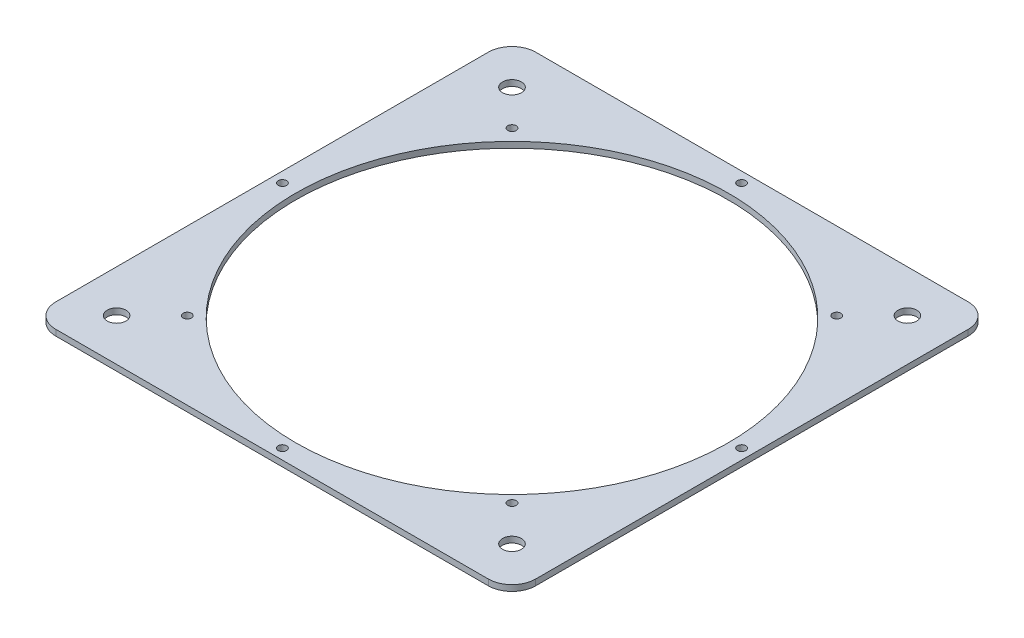
SolidWorks part; units mm, degrees
ref_plane "Front Plane" through (0, 0, 0) normal (0, 0, 1) x (1, 0, 0)
ref_plane "Top Plane" through (0, 0, 0) normal (0, 1, 0) x (1, 0, 0)
ref_plane "Right Plane" through (0, 0, 0) normal (1, 0, 0) x (0, 0, -1)
sketch "Sketch1" plane through (0, 0, 0) normal (0, 1, 0) x (1, 0, 0)
  line L1 (-128.5875, -128.5875) -> (128.5875, -128.5875)
  line L2 (-128.5875, -128.5875) -> (-128.5875, 128.5875)
  line L3 (-128.5875, 128.5875) -> (128.5875, 128.5875)
  line L4 (128.5875, -128.5875) -> (128.5875, 128.5875)
  line L5 (-128.5875, -128.5875) -> (128.5875, 128.5875) construction
  line L6 (-128.5875, 128.5875) -> (128.5875, -128.5875) construction
  point P0 (0, 0)
  dimension "D1" = 257.175
extrude "Boss-Extrude1" add sketch "Sketch1" along normal blind 3.175
sketch "Sketch2" plane through (0, 3.175, 0) normal (0, 1, 0) x (1, 0, 0)
  line L0 (-128.5875, 128.5875) -> (128.5875, -128.5875) construction
  circle A0 centre (1.0964, -1.0964) radius 115.8875
  dimension "D1" = 231.775
extrude "Cut-Extrude1" cut sketch "Sketch2" against normal blind 3.175
hole_wizard "#8 Clearance Hole1" positions "Sketch3" profile "Sketch4" hole size "#8" standard "ANSI Inch" end condition up to next
sketch "Sketch3" plane through (0, 3.175, 0) normal (0, 1, 0) x (1, 0, 0)
  line L1 (123.0376, 0) -> (87.0007, 87.0007) construction
  line L2 (87.0007, 87.0007) -> (0, 123.0376) construction
  line L3 (0, 123.0376) -> (-87.0007, 87.0007) construction
  line L4 (-87.0007, 87.0007) -> (-123.0376, 0) construction
  line L5 (-123.0376, 0) -> (-87.0007, -87.0007) construction
  line L6 (-87.0007, -87.0007) -> (0, -123.0376) construction
  line L7 (0, -123.0376) -> (87.0007, -87.0007) construction
  line L8 (87.0007, -87.0007) -> (123.0376, 0) construction
  circle A0 centre (0, 0) radius 123.0376 construction
  circle A1 centre (0, 0) radius 113.6719 construction
  point P6 (123.0376, 0)
  point P7 (87.0007, 87.0007)
  point P8 (0, 123.0376)
  point P9 (-87.0007, 87.0007)
  point P10 (-123.0376, 0)
  point P11 (-87.0007, -87.0007)
  point P12 (0, -123.0376)
  point P13 (87.0007, -87.0007)
  dimension "D1" = 246.0752
sketch "Sketch4" plane through (87.0007, 3.175, 87.0007) normal (1, 0, 0) x (0, 0, 1)
  line L0 (0, 0) -> (0, 3.175)
  line L1 (0, 3.175) -> (2.2479, 3.175)
  line L2 (2.2479, 3.175) -> (2.2479, 0)
  line L5 (2.2479, 0) -> (0, 0)
  line L11 (0, -6.35) -> (0, 107.95) construction
  dimension "Thru Hole Dia." = 4.4958
  dimension "Thru Hole Depth" = 3.175
fillet "Fillet1" radius 12.7 4 edges at (-128.5875, 1.5875, -128.5875) (-128.5875, 1.5875, 128.5875) (128.5875, 1.5875, 128.5875) (128.5875, 1.5875, -128.5875)
hole_wizard "3/8 Clearance Hole1" positions "Sketch7" profile "Sketch8" hole size "3/8" standard "ANSI Inch" end condition up to next
sketch "Sketch7" plane through (0, 3.175, 0) normal (0, 1, 0) x (1, 0, 0)
  line L9 (-124.8678, 124.8678) -> (124.8678, 124.8678) construction
  line L10 (-124.8678, 124.8678) -> (-124.8678, -124.8678) construction
  line L11 (-124.8678, -124.8678) -> (124.8678, -124.8678) construction
  line L12 (124.8678, 124.8678) -> (124.8678, -124.8678) construction
  line L15 (87.0007, 87.0007) -> (124.8678, 124.8678) construction
  line L16 (87.0007, -87.0007) -> (124.8678, -124.8678) construction
  line L18 (-87.0007, -87.0007) -> (-124.8678, -124.8678) construction
  line L20 (-87.0007, 87.0007) -> (-124.8678, 124.8678) construction
  arc A0 (115.8875, -128.5875) -> (128.5875, -115.8875) centre (115.8875, -115.8875) ccw construction
  point P307 (105.9342, 105.9342)
  point P322 (-105.9342, -105.9342)
  point P324 (-105.9342, 105.9342)
  point P326 (105.9342, -105.9342)
sketch "Sketch8" plane through (105.9342, 3.175, 105.9342) normal (1, 0, 0) x (0, 0, 1)
  line L0 (0, 0) -> (0, 3.175)
  line L1 (0, 3.175) -> (5.0419, 3.175)
  line L2 (5.0419, 3.175) -> (5.0419, 0)
  line L5 (5.0419, 0) -> (0, 0)
  line L11 (0, -6.35) -> (0, 107.95) construction
  dimension "Thru Hole Dia." = 10.0838
  dimension "Thru Hole Depth" = 3.175
